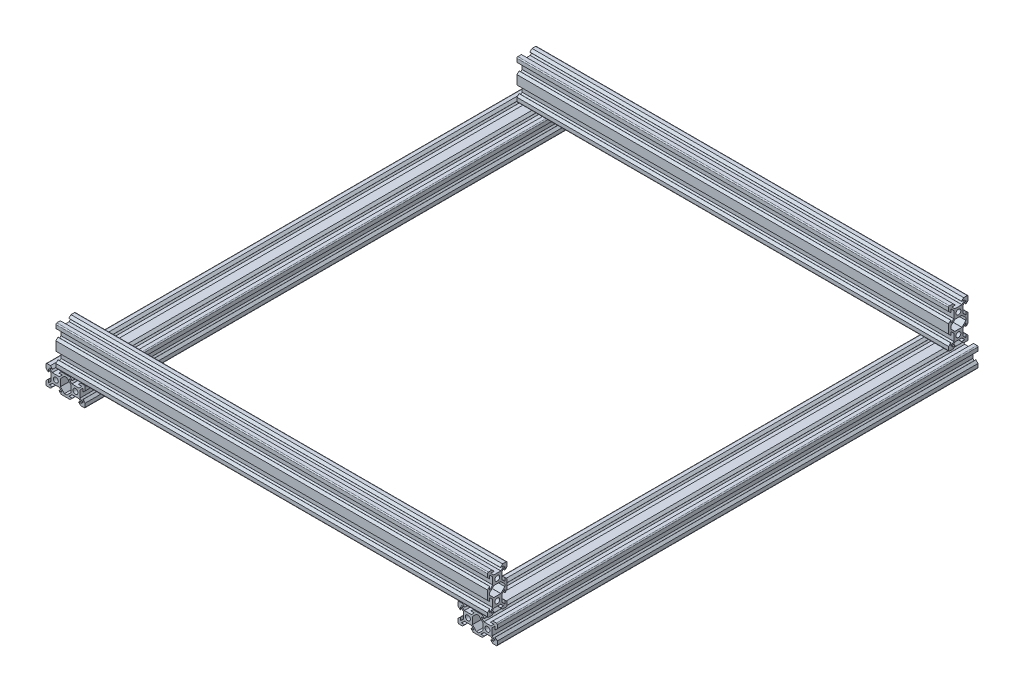
SolidWorks part; units mm, degrees
ref_plane "Alzado" through (0, 0, 0) normal (0, 0, 1) x (1, 0, 0)
ref_plane "Planta" through (0, 0, 0) normal (0, 1, 0) x (1, 0, 0)
ref_plane "Vista lateral" through (0, 0, 0) normal (1, 0, 0) x (0, 0, -1)
sketch "Archivos locales1" plane through (0, 0, 0) normal (0, 1, 0) x (1, 0, 0)
  line L0 (-210, 245) -> (-210, -245)
  line L1 (0, 0) -> (-154.8963, 0) construction
  line L2 (0, 193.8413) -> (0, -223.4944) construction
  line L3 (210, 245) -> (210, -245)
  dimension "D1" = 490
  dimension "D2" = 210
  dimension "D3" = 245
ref_plane "Plano2" through (0, 30, 0) normal (0, 1, 0) x (1, 0, 0)
sketch "Archivos locales3" plane through (0, 30, 0) normal (0, 1, 0) x (1, 0, 0)
  line L0 (-220, 235) -> (220, 235)
  line L1 (-154.8963, 0) -> (0, 0) construction
  line L2 (-220, -235) -> (220, -235)
  dimension "D1" = 10
  dimension "D2" = 10
  dimension "D3" = 10
other "Miembro estructural3"
ref_plane "Plano5" through (-220, 30, -235) normal (1, 0, 0) x (0, 1, 0)
sketch "Croquis4" plane through (-220, 30, -235) normal (1, 0, 0) x (0, 1, 0)
  line L0 (0, 10) -> (0, 7.6897) construction
  line L1 (-19, -10) -> (-15.4103, -10)
  line L2 (-20, -9) -> (-20, -5.4103)
  line L3 (-19, 10) -> (-15.4103, 10)
  line L5 (20, 5.4103) -> (20, 9)
  line L6 (20, 5.4103) -> (17.8604, 3.2707)
  line L8 (17.6897, 3.3414) -> (17.6897, 6.3586)
  line L9 (-15.4103, 10) -> (-13.2707, 7.8604)
  line L10 (-13.3414, 7.6897) -> (-16.3586, 7.6897)
  line L11 (-16.4293, 7.519) -> (-13.6293, 4.719)
  line L12 (-13.5586, 4.6897) -> (-6.4414, 4.6897)
  line L13 (-3.5707, 7.519) -> (-6.3707, 4.719)
  line L14 (-6.6586, 7.6897) -> (-3.6414, 7.6897)
  line L15 (-4.5897, 10) -> (-6.7293, 7.8604)
  line L16 (-4.5897, 10) -> (4.5897, 10)
  line L17 (17.519, 6.4293) -> (14.719, 3.6293)
  line L18 (14.6897, -3.5586) -> (14.6897, 3.5586)
  line L19 (-2.481, 6.4293) -> (-5.281, 3.6293)
  line L20 (-5.3103, 3.5586) -> (-5.3103, -3.5586)
  line L21 (-2.481, -6.4293) -> (-5.281, -3.6293)
  line L22 (17.519, -6.4293) -> (14.719, -3.6293)
  line L23 (17.6897, -3.3414) -> (17.6897, -6.3586)
  line L24 (-4.5897, -10) -> (-6.7293, -7.8604)
  line L25 (-6.6586, -7.6897) -> (-3.6414, -7.6897)
  line L26 (-3.5707, -7.519) -> (-6.3707, -4.719)
  line L27 (-6.4414, -4.6897) -> (-13.5586, -4.6897)
  line L28 (-16.4293, -7.519) -> (-13.6293, -4.719)
  line L29 (-13.3414, -7.6897) -> (-16.3586, -7.6897)
  line L30 (-15.4103, -10) -> (-13.2707, -7.8604)
  line L31 (-20, -5.4103) -> (-17.8604, -3.2707)
  line L32 (-17.6897, -3.3414) -> (-17.6897, -6.3586)
  line L33 (-17.519, -6.4293) -> (-14.719, -3.6293)
  line L34 (-14.6897, -3.5586) -> (-14.6897, 3.5586)
  line L35 (-17.519, 6.4293) -> (-14.719, 3.6293)
  line L36 (-17.6897, 3.3414) -> (-17.6897, 6.3586)
  line L37 (-20, 5.4103) -> (-17.8604, 3.2707)
  line L38 (-20, 5.4103) -> (-20, 9)
  line L39 (-4.5897, -10) -> (4.5897, -10)
  line L40 (-2.3103, 3.3414) -> (-2.3103, 6.3586) [skipped]
  line L41 (0, 5.4103) -> (-2.1396, 3.2707) [skipped]
  line L42 (-2.3103, -3.3414) -> (-2.3103, -6.3586) [skipped]
  line L43 (0, -5.4103) -> (-2.1396, -3.2707) [skipped]
  line L44 (20, -5.4103) -> (17.8604, -3.2707)
  line L45 (15.4103, -10) -> (13.2707, -7.8604)
  line L46 (13.3414, -7.6897) -> (16.3586, -7.6897)
  line L47 (16.4293, -7.519) -> (13.6293, -4.719)
  line L48 (6.4414, -4.6897) -> (13.5586, -4.6897)
  line L49 (3.5707, -7.519) -> (6.3707, -4.719)
  line L50 (6.6586, -7.6897) -> (3.6414, -7.6897)
  line L51 (4.5897, -10) -> (6.7293, -7.8604)
  line L52 (2.481, -6.4293) -> (5.281, -3.6293)
  line L53 (5.3103, 3.5586) -> (5.3103, -3.5586)
  line L54 (2.481, 6.4293) -> (5.281, 3.6293)
  line L55 (4.5897, 10) -> (6.7293, 7.8604)
  line L56 (6.6586, 7.6897) -> (3.6414, 7.6897)
  line L57 (3.5707, 7.519) -> (6.3707, 4.719)
  line L58 (13.5586, 4.6897) -> (6.4414, 4.6897)
  line L59 (16.4293, 7.519) -> (13.6293, 4.719)
  line L60 (13.3414, 7.6897) -> (16.3586, 7.6897)
  line L61 (15.4103, 10) -> (13.2707, 7.8604)
  line L62 (19, 10) -> (15.4103, 10)
  line L63 (20, -9) -> (20, -5.4103)
  line L64 (19, -10) -> (15.4103, -10)
  line L65 (-3.6414, -7.6897) -> (3.6414, -7.6897) construction
  line L69 (-2.481, -6.4293) -> (-1.2206, -7.6897)
  line L70 (-1.2206, -7.6897) -> (1.2206, -7.6897)
  line L71 (2.481, -6.4293) -> (1.2206, -7.6897)
  line L72 (-2.481, 6.4293) -> (-1.2206, 7.6897)
  line L73 (-1.2206, 7.6897) -> (1.2206, 7.6897)
  line L74 (1.2206, 7.6897) -> (2.481, 6.4293)
  arc A0 (17.6897, 3.3414) -> (17.8604, 3.2707) centre (17.7897, 3.3414) ccw
  arc A1 (17.519, 6.4293) -> (17.6897, 6.3586) centre (17.5897, 6.3586) cw
  arc A2 (-19, -10) -> (-20, -9) centre (-19, -9) cw
  arc A3 (-20, 9) -> (-19, 10) centre (-19, 9) cw
  circle A4 centre (-10, 0) radius 2.5
  arc A5 (14.719, 3.6293) -> (14.6897, 3.5586) centre (14.7897, 3.5586) ccw
  arc A6 (-6.6586, 7.6897) -> (-6.7293, 7.8604) centre (-6.6586, 7.7897) cw
  arc A7 (-13.2707, 7.8604) -> (-13.3414, 7.6897) centre (-13.3414, 7.7897) cw
  arc A8 (-3.5707, 7.519) -> (-3.6414, 7.6897) centre (-3.6414, 7.5897) ccw
  arc A9 (-6.3707, 4.719) -> (-6.4414, 4.6897) centre (-6.4414, 4.7897) cw
  arc A10 (-13.6293, 4.719) -> (-13.5586, 4.6897) centre (-13.5586, 4.7897) ccw
  arc A11 (-16.3586, 7.6897) -> (-16.4293, 7.519) centre (-16.3586, 7.5897) ccw
  arc A12 (14.719, -3.6293) -> (14.6897, -3.5586) centre (14.7897, -3.5586) cw
  arc A13 (17.6897, -6.3586) -> (17.519, -6.4293) centre (17.5897, -6.3586) cw
  arc A14 (-5.281, 3.6293) -> (-5.3103, 3.5586) centre (-5.2103, 3.5586) ccw
  arc A15 (-5.281, -3.6293) -> (-5.3103, -3.5586) centre (-5.2103, -3.5586) cw
  arc A16 (17.8604, -3.2707) -> (17.6897, -3.3414) centre (17.7897, -3.3414) ccw
  arc A17 (13.3414, -7.6897) -> (13.2707, -7.8604) centre (13.3414, -7.7897) ccw
  arc A18 (-6.7293, -7.8604) -> (-6.6586, -7.6897) centre (-6.6586, -7.7897) cw
  arc A19 (-3.6414, -7.6897) -> (-3.5707, -7.519) centre (-3.6414, -7.5897) ccw
  arc A20 (-6.3707, -4.719) -> (-6.4414, -4.6897) centre (-6.4414, -4.7897) ccw
  arc A21 (-13.6293, -4.719) -> (-13.5586, -4.6897) centre (-13.5586, -4.7897) cw
  arc A22 (-16.4293, -7.519) -> (-16.3586, -7.6897) centre (-16.3586, -7.5897) ccw
  arc A23 (-13.3414, -7.6897) -> (-13.2707, -7.8604) centre (-13.3414, -7.7897) cw
  arc A24 (-17.8604, -3.2707) -> (-17.6897, -3.3414) centre (-17.7897, -3.3414) cw
  arc A25 (-17.6897, -6.3586) -> (-17.519, -6.4293) centre (-17.5897, -6.3586) ccw
  arc A26 (-14.719, -3.6293) -> (-14.6897, -3.5586) centre (-14.7897, -3.5586) ccw
  arc A27 (-14.719, 3.6293) -> (-14.6897, 3.5586) centre (-14.7897, 3.5586) cw
  arc A28 (-17.519, 6.4293) -> (-17.6897, 6.3586) centre (-17.5897, 6.3586) ccw
  arc A29 (-17.6897, 3.3414) -> (-17.8604, 3.2707) centre (-17.7897, 3.3414) cw
  arc A30 (-2.3103, 6.3586) -> (-2.481, 6.4293) centre (-2.4103, 6.3586) ccw [skipped]
  arc A31 (-2.1396, 3.2707) -> (-2.3103, 3.3414) centre (-2.2103, 3.3414) cw [skipped]
  arc A32 (-2.481, -6.4293) -> (-2.3103, -6.3586) centre (-2.4103, -6.3586) ccw [skipped]
  arc A33 (-2.3103, -3.3414) -> (-2.1396, -3.2707) centre (-2.2103, -3.3414) cw [skipped]
  arc A34 (16.4293, -7.519) -> (16.3586, -7.6897) centre (16.3586, -7.5897) cw
  arc A35 (13.6293, -4.719) -> (13.5586, -4.6897) centre (13.5586, -4.7897) ccw
  arc A36 (6.3707, -4.719) -> (6.4414, -4.6897) centre (6.4414, -4.7897) cw
  arc A37 (3.6414, -7.6897) -> (3.5707, -7.519) centre (3.6414, -7.5897) cw
  arc A38 (6.7293, -7.8604) -> (6.6586, -7.6897) centre (6.6586, -7.7897) ccw
  arc A39 (5.281, -3.6293) -> (5.3103, -3.5586) centre (5.2103, -3.5586) ccw
  arc A40 (5.281, 3.6293) -> (5.3103, 3.5586) centre (5.2103, 3.5586) cw
  arc A41 (16.3586, 7.6897) -> (16.4293, 7.519) centre (16.3586, 7.5897) cw
  arc A42 (13.6293, 4.719) -> (13.5586, 4.6897) centre (13.5586, 4.7897) cw
  arc A43 (6.3707, 4.719) -> (6.4414, 4.6897) centre (6.4414, 4.7897) ccw
  arc A44 (3.5707, 7.519) -> (3.6414, 7.6897) centre (3.6414, 7.5897) cw
  arc A45 (13.2707, 7.8604) -> (13.3414, 7.6897) centre (13.3414, 7.7897) ccw
  arc A46 (6.6586, 7.6897) -> (6.7293, 7.8604) centre (6.6586, 7.7897) ccw
  circle A47 centre (10, 0) radius 2.5
  arc A48 (20, 9) -> (19, 10) centre (19, 9) ccw
  arc A49 (19, -10) -> (20, -9) centre (19, -9) ccw
  point P0 (0, 0)
  point P2 (0, 0)
  point P34 (-10, 4.6897)
  point P39 (-6.9, 7.6897)
  point P42 (-13.1, 7.6897)
  point P45 (-3.4, 7.6897)
  point P48 (-6.4, 4.6897)
  point P51 (-13.6, 4.6897)
  point P54 (-16.6, 7.6897)
  point P118 (-10, 0)
  point P188 (16.6, 7.6897)
  point P189 (13.6, 4.6897)
  point P190 (6.4, 4.6897)
  point P191 (3.4, 7.6897)
  point P192 (13.1, 7.6897)
  point P193 (6.9, 7.6897)
  point P194 (10, 4.6897)
  point P200 (0, -7.6897)
  dimension "D5" = 5
  dimension "D10" = 0.1
  dimension "D11" = 0.1
  dimension "D7" = 3
  dimension "D8" = 3.5
  dimension "D9" = 45
  dimension "D12" = 4
other "Miembro estructural4"
ref_plane "Plano6" through (-210, 0, -245) normal (0, 0, 1) x (1, 0, 0)
sketch "Croquis41" plane through (-210, 0, -245) normal (0, 0, 1) x (1, 0, 0)
  line L0 (0, 10) -> (0, 7.6897) construction
  line L1 (-19, -10) -> (-15.4103, -10)
  line L2 (-20, -9) -> (-20, -5.4103)
  line L3 (-19, 10) -> (-15.4103, 10)
  line L5 (20, 5.4103) -> (20, 9)
  line L6 (20, 5.4103) -> (17.8604, 3.2707)
  line L8 (17.6897, 3.3414) -> (17.6897, 6.3586)
  line L9 (-15.4103, 10) -> (-13.2707, 7.8604)
  line L10 (-13.3414, 7.6897) -> (-16.3586, 7.6897)
  line L11 (-16.4293, 7.519) -> (-13.6293, 4.719)
  line L12 (-13.5586, 4.6897) -> (-6.4414, 4.6897)
  line L13 (-3.5707, 7.519) -> (-6.3707, 4.719)
  line L14 (-6.6586, 7.6897) -> (-3.6414, 7.6897)
  line L15 (-4.5897, 10) -> (-6.7293, 7.8604)
  line L16 (-4.5897, 10) -> (4.5897, 10)
  line L17 (17.519, 6.4293) -> (14.719, 3.6293)
  line L18 (14.6897, -3.5586) -> (14.6897, 3.5586)
  line L19 (-2.481, 6.4293) -> (-5.281, 3.6293)
  line L20 (-5.3103, 3.5586) -> (-5.3103, -3.5586)
  line L21 (-2.481, -6.4293) -> (-5.281, -3.6293)
  line L22 (17.519, -6.4293) -> (14.719, -3.6293)
  line L23 (17.6897, -3.3414) -> (17.6897, -6.3586)
  line L24 (-4.5897, -10) -> (-6.7293, -7.8604)
  line L25 (-6.6586, -7.6897) -> (-3.6414, -7.6897)
  line L26 (-3.5707, -7.519) -> (-6.3707, -4.719)
  line L27 (-6.4414, -4.6897) -> (-13.5586, -4.6897)
  line L28 (-16.4293, -7.519) -> (-13.6293, -4.719)
  line L29 (-13.3414, -7.6897) -> (-16.3586, -7.6897)
  line L30 (-15.4103, -10) -> (-13.2707, -7.8604)
  line L31 (-20, -5.4103) -> (-17.8604, -3.2707)
  line L32 (-17.6897, -3.3414) -> (-17.6897, -6.3586)
  line L33 (-17.519, -6.4293) -> (-14.719, -3.6293)
  line L34 (-14.6897, -3.5586) -> (-14.6897, 3.5586)
  line L35 (-17.519, 6.4293) -> (-14.719, 3.6293)
  line L36 (-17.6897, 3.3414) -> (-17.6897, 6.3586)
  line L37 (-20, 5.4103) -> (-17.8604, 3.2707)
  line L38 (-20, 5.4103) -> (-20, 9)
  line L39 (-4.5897, -10) -> (4.5897, -10)
  line L40 (-2.3103, 3.3414) -> (-2.3103, 6.3586) [skipped]
  line L41 (0, 5.4103) -> (-2.1396, 3.2707) [skipped]
  line L42 (-2.3103, -3.3414) -> (-2.3103, -6.3586) [skipped]
  line L43 (0, -5.4103) -> (-2.1396, -3.2707) [skipped]
  line L44 (20, -5.4103) -> (17.8604, -3.2707)
  line L45 (15.4103, -10) -> (13.2707, -7.8604)
  line L46 (13.3414, -7.6897) -> (16.3586, -7.6897)
  line L47 (16.4293, -7.519) -> (13.6293, -4.719)
  line L48 (6.4414, -4.6897) -> (13.5586, -4.6897)
  line L49 (3.5707, -7.519) -> (6.3707, -4.719)
  line L50 (6.6586, -7.6897) -> (3.6414, -7.6897)
  line L51 (4.5897, -10) -> (6.7293, -7.8604)
  line L52 (2.481, -6.4293) -> (5.281, -3.6293)
  line L53 (5.3103, 3.5586) -> (5.3103, -3.5586)
  line L54 (2.481, 6.4293) -> (5.281, 3.6293)
  line L55 (4.5897, 10) -> (6.7293, 7.8604)
  line L56 (6.6586, 7.6897) -> (3.6414, 7.6897)
  line L57 (3.5707, 7.519) -> (6.3707, 4.719)
  line L58 (13.5586, 4.6897) -> (6.4414, 4.6897)
  line L59 (16.4293, 7.519) -> (13.6293, 4.719)
  line L60 (13.3414, 7.6897) -> (16.3586, 7.6897)
  line L61 (15.4103, 10) -> (13.2707, 7.8604)
  line L62 (19, 10) -> (15.4103, 10)
  line L63 (20, -9) -> (20, -5.4103)
  line L64 (19, -10) -> (15.4103, -10)
  line L65 (-3.6414, -7.6897) -> (3.6414, -7.6897) construction
  line L69 (-2.481, -6.4293) -> (-1.2206, -7.6897)
  line L70 (-1.2206, -7.6897) -> (1.2206, -7.6897)
  line L71 (2.481, -6.4293) -> (1.2206, -7.6897)
  line L72 (-2.481, 6.4293) -> (-1.2206, 7.6897)
  line L73 (-1.2206, 7.6897) -> (1.2206, 7.6897)
  line L74 (1.2206, 7.6897) -> (2.481, 6.4293)
  arc A0 (17.6897, 3.3414) -> (17.8604, 3.2707) centre (17.7897, 3.3414) ccw
  arc A1 (17.519, 6.4293) -> (17.6897, 6.3586) centre (17.5897, 6.3586) cw
  arc A2 (-19, -10) -> (-20, -9) centre (-19, -9) cw
  arc A3 (-20, 9) -> (-19, 10) centre (-19, 9) cw
  circle A4 centre (-10, 0) radius 2.5
  arc A5 (14.719, 3.6293) -> (14.6897, 3.5586) centre (14.7897, 3.5586) ccw
  arc A6 (-6.6586, 7.6897) -> (-6.7293, 7.8604) centre (-6.6586, 7.7897) cw
  arc A7 (-13.2707, 7.8604) -> (-13.3414, 7.6897) centre (-13.3414, 7.7897) cw
  arc A8 (-3.5707, 7.519) -> (-3.6414, 7.6897) centre (-3.6414, 7.5897) ccw
  arc A9 (-6.3707, 4.719) -> (-6.4414, 4.6897) centre (-6.4414, 4.7897) cw
  arc A10 (-13.6293, 4.719) -> (-13.5586, 4.6897) centre (-13.5586, 4.7897) ccw
  arc A11 (-16.3586, 7.6897) -> (-16.4293, 7.519) centre (-16.3586, 7.5897) ccw
  arc A12 (14.719, -3.6293) -> (14.6897, -3.5586) centre (14.7897, -3.5586) cw
  arc A13 (17.6897, -6.3586) -> (17.519, -6.4293) centre (17.5897, -6.3586) cw
  arc A14 (-5.281, 3.6293) -> (-5.3103, 3.5586) centre (-5.2103, 3.5586) ccw
  arc A15 (-5.281, -3.6293) -> (-5.3103, -3.5586) centre (-5.2103, -3.5586) cw
  arc A16 (17.8604, -3.2707) -> (17.6897, -3.3414) centre (17.7897, -3.3414) ccw
  arc A17 (13.3414, -7.6897) -> (13.2707, -7.8604) centre (13.3414, -7.7897) ccw
  arc A18 (-6.7293, -7.8604) -> (-6.6586, -7.6897) centre (-6.6586, -7.7897) cw
  arc A19 (-3.6414, -7.6897) -> (-3.5707, -7.519) centre (-3.6414, -7.5897) ccw
  arc A20 (-6.3707, -4.719) -> (-6.4414, -4.6897) centre (-6.4414, -4.7897) ccw
  arc A21 (-13.6293, -4.719) -> (-13.5586, -4.6897) centre (-13.5586, -4.7897) cw
  arc A22 (-16.4293, -7.519) -> (-16.3586, -7.6897) centre (-16.3586, -7.5897) ccw
  arc A23 (-13.3414, -7.6897) -> (-13.2707, -7.8604) centre (-13.3414, -7.7897) cw
  arc A24 (-17.8604, -3.2707) -> (-17.6897, -3.3414) centre (-17.7897, -3.3414) cw
  arc A25 (-17.6897, -6.3586) -> (-17.519, -6.4293) centre (-17.5897, -6.3586) ccw
  arc A26 (-14.719, -3.6293) -> (-14.6897, -3.5586) centre (-14.7897, -3.5586) ccw
  arc A27 (-14.719, 3.6293) -> (-14.6897, 3.5586) centre (-14.7897, 3.5586) cw
  arc A28 (-17.519, 6.4293) -> (-17.6897, 6.3586) centre (-17.5897, 6.3586) ccw
  arc A29 (-17.6897, 3.3414) -> (-17.8604, 3.2707) centre (-17.7897, 3.3414) cw
  arc A30 (-2.3103, 6.3586) -> (-2.481, 6.4293) centre (-2.4103, 6.3586) ccw [skipped]
  arc A31 (-2.1396, 3.2707) -> (-2.3103, 3.3414) centre (-2.2103, 3.3414) cw [skipped]
  arc A32 (-2.481, -6.4293) -> (-2.3103, -6.3586) centre (-2.4103, -6.3586) ccw [skipped]
  arc A33 (-2.3103, -3.3414) -> (-2.1396, -3.2707) centre (-2.2103, -3.3414) cw [skipped]
  arc A34 (16.4293, -7.519) -> (16.3586, -7.6897) centre (16.3586, -7.5897) cw
  arc A35 (13.6293, -4.719) -> (13.5586, -4.6897) centre (13.5586, -4.7897) ccw
  arc A36 (6.3707, -4.719) -> (6.4414, -4.6897) centre (6.4414, -4.7897) cw
  arc A37 (3.6414, -7.6897) -> (3.5707, -7.519) centre (3.6414, -7.5897) cw
  arc A38 (6.7293, -7.8604) -> (6.6586, -7.6897) centre (6.6586, -7.7897) ccw
  arc A39 (5.281, -3.6293) -> (5.3103, -3.5586) centre (5.2103, -3.5586) ccw
  arc A40 (5.281, 3.6293) -> (5.3103, 3.5586) centre (5.2103, 3.5586) cw
  arc A41 (16.3586, 7.6897) -> (16.4293, 7.519) centre (16.3586, 7.5897) cw
  arc A42 (13.6293, 4.719) -> (13.5586, 4.6897) centre (13.5586, 4.7897) cw
  arc A43 (6.3707, 4.719) -> (6.4414, 4.6897) centre (6.4414, 4.7897) ccw
  arc A44 (3.5707, 7.519) -> (3.6414, 7.6897) centre (3.6414, 7.5897) cw
  arc A45 (13.2707, 7.8604) -> (13.3414, 7.6897) centre (13.3414, 7.7897) ccw
  arc A46 (6.6586, 7.6897) -> (6.7293, 7.8604) centre (6.6586, 7.7897) ccw
  circle A47 centre (10, 0) radius 2.5
  arc A48 (20, 9) -> (19, 10) centre (19, 9) ccw
  arc A49 (19, -10) -> (20, -9) centre (19, -9) ccw
  point P0 (0, 0)
  point P2 (0, 0)
  point P34 (-10, 4.6897)
  point P39 (-6.9, 7.6897)
  point P42 (-13.1, 7.6897)
  point P45 (-3.4, 7.6897)
  point P48 (-6.4, 4.6897)
  point P51 (-13.6, 4.6897)
  point P54 (-16.6, 7.6897)
  point P118 (-10, 0)
  point P188 (16.6, 7.6897)
  point P189 (13.6, 4.6897)
  point P190 (6.4, 4.6897)
  point P191 (3.4, 7.6897)
  point P192 (13.1, 7.6897)
  point P193 (6.9, 7.6897)
  point P194 (10, 4.6897)
  point P200 (0, -7.6897)
  dimension "D5" = 5
  dimension "D10" = 0.1
  dimension "D11" = 0.1
  dimension "D7" = 3
  dimension "D8" = 3.5
  dimension "D9" = 45
  dimension "D12" = 4
